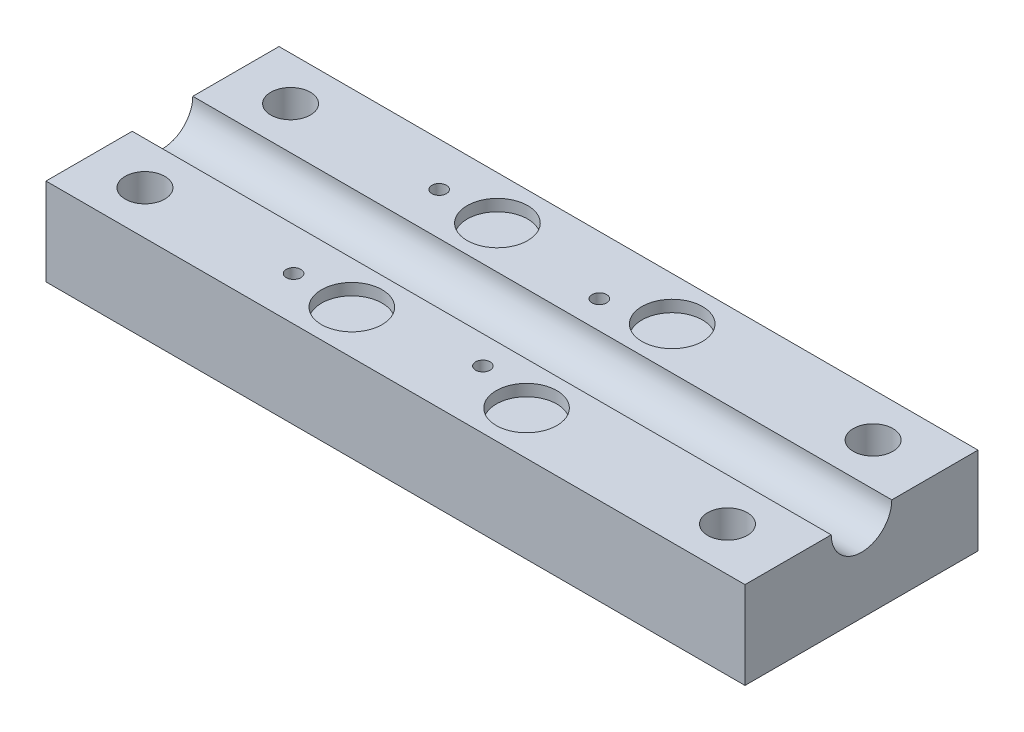
SolidWorks part; units mm, degrees
ref_plane "Front Plane" through (0, 0, 0) normal (0, 0, 1) x (1, 0, 0)
ref_plane "Top Plane" through (0, 0, 0) normal (0, 1, 0) x (1, 0, 0)
ref_plane "Right Plane" through (0, 0, 0) normal (1, 0, 0) x (0, 0, -1)
sketch "Sketch1" plane through (0, 0, 0) normal (0, 1, 0) x (1, 0, 0)
  line L1 (-38.1, 12.7) -> (38.1, 12.7)
  line L2 (-38.1, 12.7) -> (-38.1, -12.7)
  line L3 (-38.1, -12.7) -> (38.1, -12.7)
  line L4 (38.1, 12.7) -> (38.1, -12.7)
  dimension "D1" = 25.4
  dimension "D2" = 76.2
  dimension "D3" = 38.1
  dimension "D4" = 12.7
extrude "Boss-Extrude1" add sketch "Sketch1" along normal blind 9.525
sketch "Sketch2" plane through (0, 9.525, 0) normal (0, 1, 0) x (1, 0, 0)
  circle A0 centre (-32.0741, 7.9375) radius 2.159
  circle A1 centre (-32.0741, -7.9375) radius 2.159
  circle A2 centre (31.4259, 7.9375) radius 2.159
  circle A3 centre (31.4259, -7.9375) radius 2.159
  dimension "D1" = 4.318
  dimension "D2" = 15.875
  dimension "D3" = 63.5
  dimension "D4" = 32.0741
  dimension "D5" = 7.9375
extrude "Cut-Extrude1" cut sketch "Sketch2" against normal through all
sketch "Sketch3" plane through (0, 9.525, 0) normal (0, 1, 0) x (1, 0, 0)
  circle A0 centre (-9.525, 7.9375) radius 3.302
  circle A1 centre (-9.525, -7.9375) radius 3.302
  circle A2 centre (9.525, -7.9375) radius 3.302
  circle A3 centre (9.525, 7.9375) radius 3.302
  dimension "D1" = 6.604
  dimension "D2" = 15.875
  dimension "D3" = 19.05
  dimension "D4" = 7.9375
  dimension "D5" = 9.525
extrude "Cut-Extrude2" cut sketch "Sketch3" against normal blind 1.27
sketch "Sketch4" plane through (0, 9.525, 0) normal (0, 1, 0) x (1, 0, 0)
  circle A0 centre (-15.875, 7.9375) radius 0.7937
  circle A1 centre (-15.875, -7.9375) radius 0.7937
  circle A2 centre (3.175, 6.35) radius 0.7937
  circle A3 centre (3.175, -6.35) radius 0.7938
  dimension "D1" = 1.5875
  dimension "D2" = 15.875
  dimension "D3" = 7.9375
  dimension "D4" = 15.875
  dimension "D5" = 12.7
  dimension "D6" = 6.35
  dimension "D7" = 3.175
extrude "Cut-Extrude3" cut sketch "Sketch4" against normal through all
sketch "Sketch5" plane through (-38.1, 0, 0) normal (-1, 0, 0) x (0, 0, 1)
  line L0 (-12.7, 9.525) -> (12.7, 9.525) construction
  circle A0 centre (0, 9.525) radius 3.302
  dimension "D1" = 6.604
extrude "Cut-Extrude4" cut sketch "Sketch5" against normal through all
